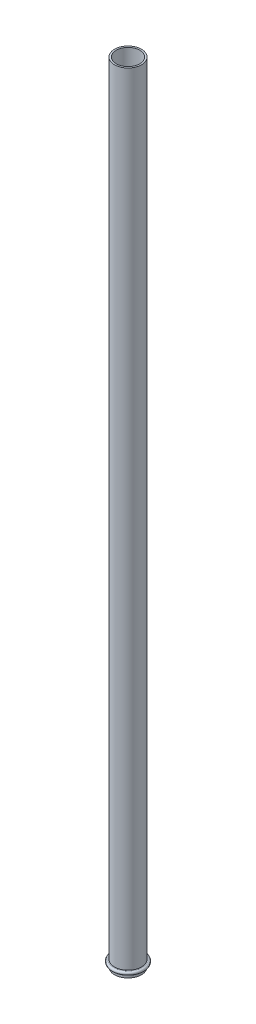
SolidWorks part; units mm, degrees
material "1060 Alloy"
ref_plane "Front Plane" through (0, 0, 0) normal (0, 0, 1) x (1, 0, 0)
ref_plane "Top Plane" through (0, 0, 0) normal (0, 1, 0) x (1, 0, 0)
ref_plane "Right Plane" through (0, 0, 0) normal (1, 0, 0) x (0, 0, -1)
sketch "Sketch1" plane through (0, 0, 0) normal (0, 1, 0) x (1, 0, 0)
  circle A0 centre (0, 0) radius 7
  circle A1 centre (0, 0) radius 8
extrude "Boss-Extrude1" add sketch "Sketch1" along normal blind 467.66
sketch "Sketch2" plane through (0, 0, 0) normal (0, 0, 1) x (1, 0, 0)
  line L0 (0, 0) -> (0, 12.5409) construction
  line L1 (8, 2) -> (8.5, 2)
  line L3 (8.5, 4) -> (8, 4)
  line L4 (8, 0) -> (8, 467.66) construction
  line L5 (8, 2) -> (8, 4)
  arc A0 (8.5, 2) -> (8.5, 4) centre (8.5, 3) ccw
revolve "Revolve1" add sketch "Sketch2" angle 360 about L0
scale "Scale1" scale about centroid uniform scaling yes scale factor 0.857143
